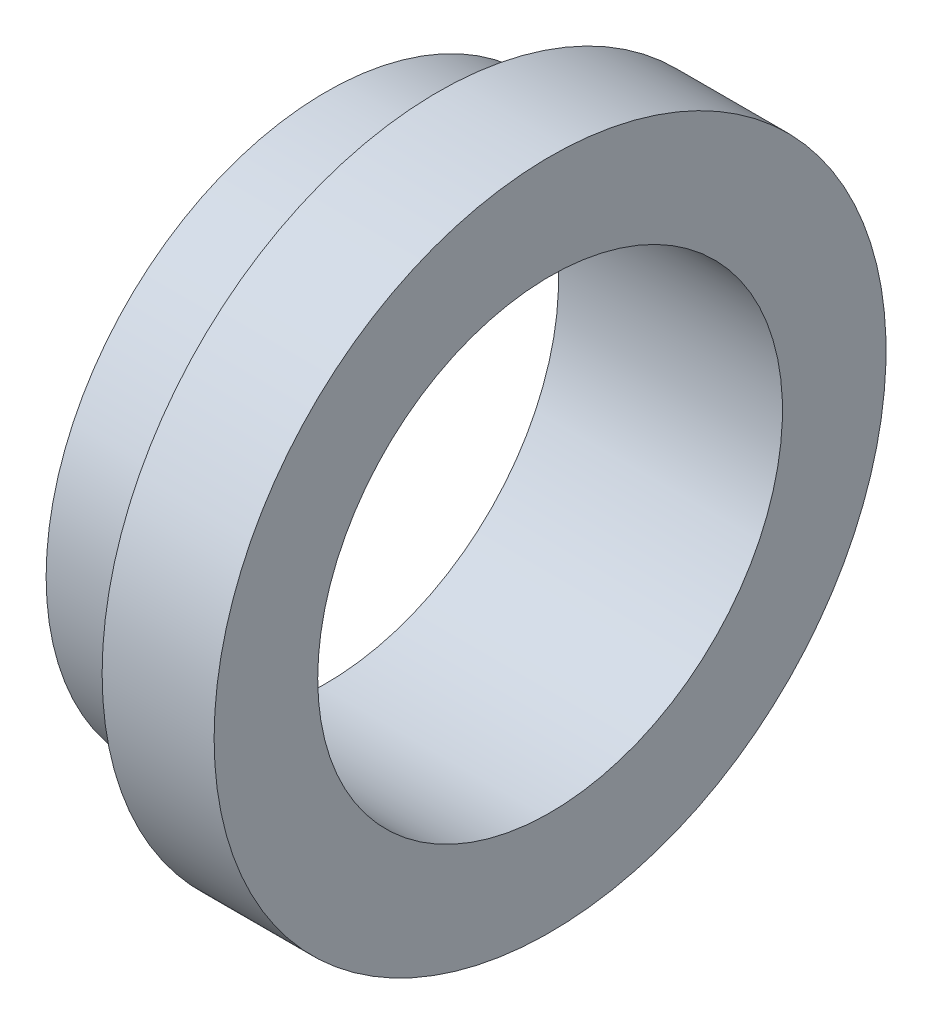
SolidWorks part; units mm, degrees
ref_plane "Front Plane" through (0, 0, 0) normal (0, 0, 1) x (1, 0, 0)
ref_plane "Top Plane" through (0, 0, 0) normal (0, 1, 0) x (1, 0, 0)
ref_plane "Right Plane" through (0, 0, 0) normal (1, 0, 0) x (0, 0, -1)
sketch "Sketch1" plane through (0, 0, 0) normal (0, 0, 1) x (1, 0, 0)
  line L0 (1.9977, 0) -> (16.3827, 0) construction
  line L1 (-1, 6) -> (1, 6)
  line L2 (-1, 6) -> (-1, -6)
  line L3 (-1, -6) -> (1, -6)
  line L4 (1, 6) -> (1, -6)
  line L5 (-1, 6) -> (1, -6) construction
  line L6 (-1, -6) -> (1, 6) construction
  line L8 (-3, 5) -> (-1, 5)
  line L9 (-3, 5) -> (-3, -5)
  line L10 (-3, -5) -> (-1, -5)
  line L11 (-1, 5) -> (-1, -5)
  line L12 (-3, 5) -> (-1, -5) construction
  line L13 (-3, -5) -> (-1, 5) construction
  line L14 (-3, 4.15) -> (1, 4.15)
  line L15 (-3, 4.15) -> (-3, -4.15)
  line L16 (-3, -4.15) -> (1, -4.15)
  line L17 (1, 4.15) -> (1, -4.15)
  line L19 (-3, -4.15) -> (1, 4.15) construction
  point P0 (0, 0)
  point P6 (-2, 0)
  point P13 (-1, 0)
  point P18 (-3, 0)
  dimension "D1" = 10
  dimension "D2" = 12
  dimension "D3" = 8.3
  dimension "D4" = 4
  dimension "D5" = 2
revolve "Revolve1" add sketch "Sketch1" angle 360 about L0
